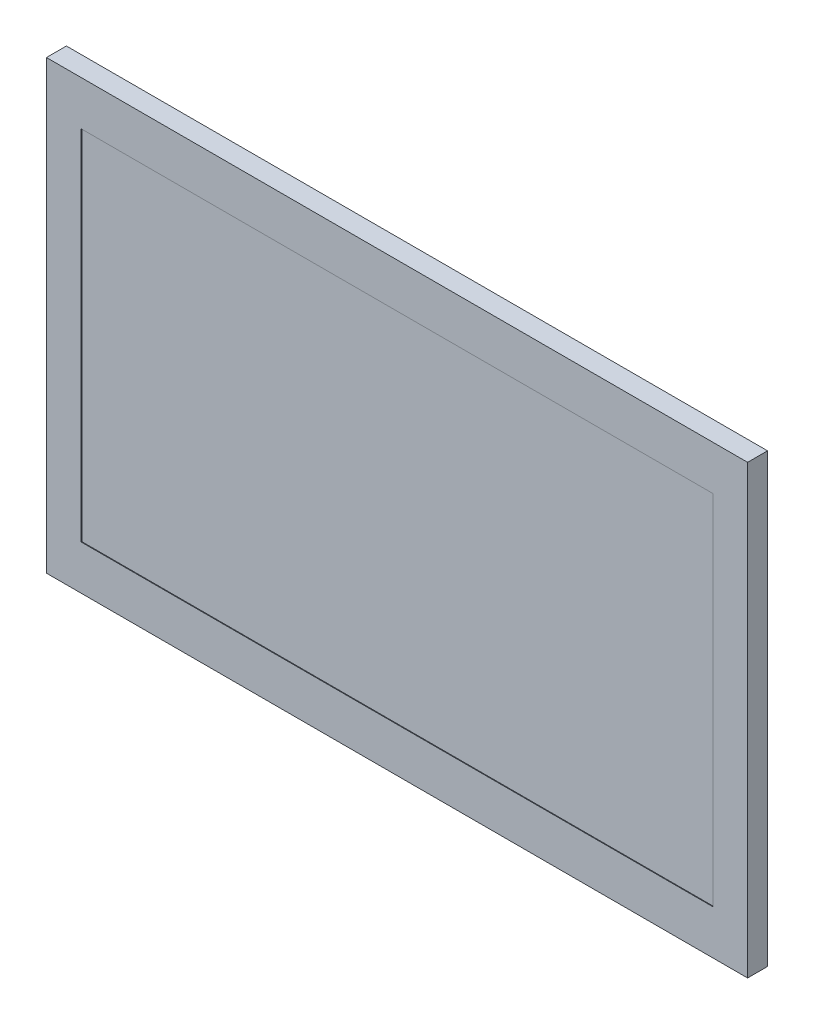
SolidWorks part; units mm, degrees
ref_plane "前视基准面" through (0, 0, 0) normal (0, 0, 1) x (1, 0, 0)
ref_plane "上视基准面" through (0, 0, 0) normal (0, 1, 0) x (1, 0, 0)
ref_plane "右视基准面" through (0, 0, 0) normal (1, 0, 0) x (0, 0, -1)
sketch "草图1" plane through (0, 0, 0) normal (0, 0, 1) x (1, 0, 0)
  line L1 (-52.75, -33.6) -> (52.75, -33.6)
  line L2 (-52.75, -33.6) -> (-52.75, 33.6)
  line L3 (-52.75, 33.6) -> (52.75, 33.6)
  line L4 (52.75, -33.6) -> (52.75, 33.6)
  line L5 (-52.75, -33.6) -> (52.75, 33.6) construction
  line L6 (-52.75, 33.6) -> (52.75, -33.6) construction
  point P0 (0, 0)
  dimension "D1" = 67.2
  dimension "D2" = 105.5
extrude "凸台-拉伸1" add sketch "草图1" along normal blind 3
sketch "草图2" plane through (0, 0, 3) normal (0, 0, 1) x (1, 0, 0)
  line L1 (-47.52, 26.925) -> (47.52, 26.925)
  line L2 (-47.52, 26.925) -> (-47.52, -26.925)
  line L3 (-47.52, -26.925) -> (47.52, -26.925)
  line L4 (47.52, 26.925) -> (47.52, -26.925)
  line L5 (-47.52, 26.925) -> (47.52, -26.925) construction
  line L6 (-47.52, -26.925) -> (47.52, 26.925) construction
  point P0 (0, 0)
  dimension "D1" = 95.04
  dimension "D2" = 53.85
extrude "切除-拉伸1" cut sketch "草图2" against normal blind 0.1
